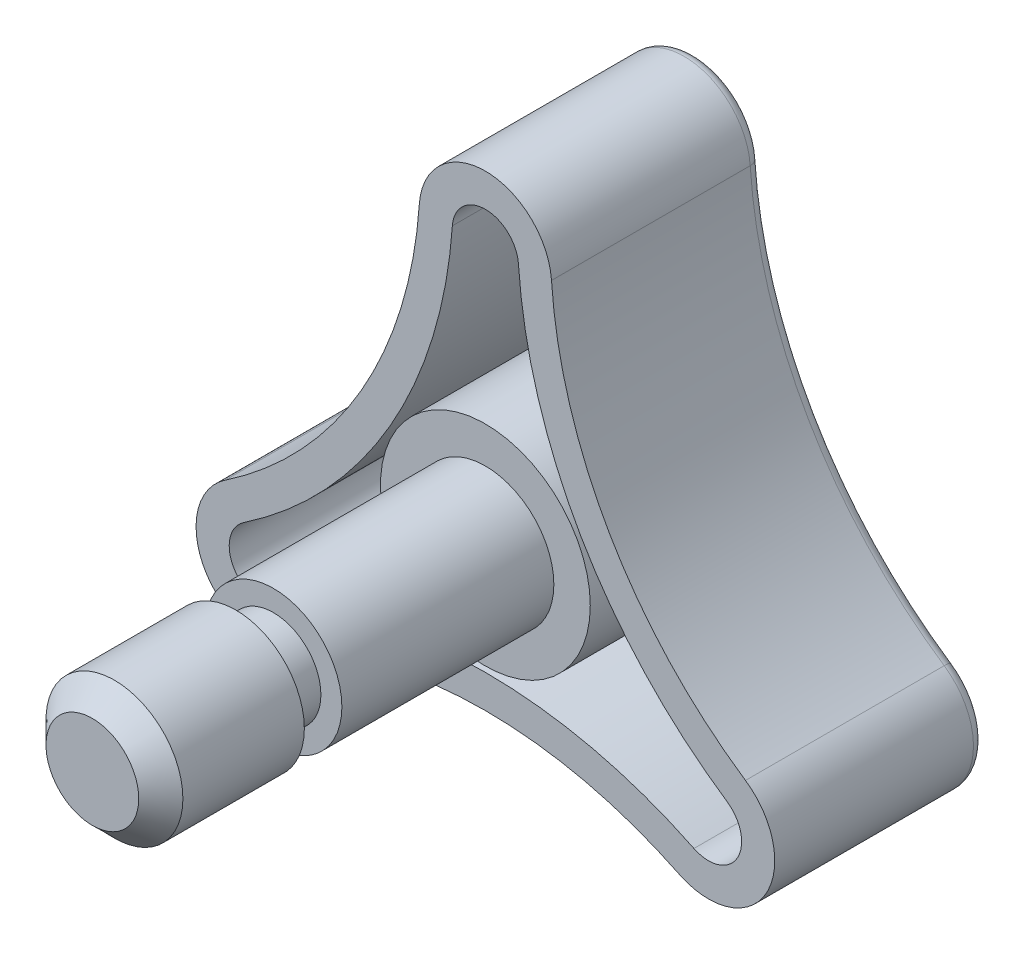
SolidWorks part; units mm, degrees
ref_plane "Front Plane" through (0, 0, 0) normal (0, 0, 1) x (1, 0, 0)
ref_plane "Top Plane" through (0, 0, 0) normal (0, 1, 0) x (1, 0, 0)
ref_plane "Right Plane" through (0, 0, 0) normal (1, 0, 0) x (0, 0, -1)
sketch "Sketch1" plane through (0, 0, 0) normal (0, 0, 1) x (1, 0, 0)
  line L0 (0, 14.6667) -> (0, -7.3333) construction
  line L1 (0, 14.6667) -> (-12.7017, -7.3333) construction
  line L2 (-12.7017, -7.3333) -> (12.7017, -7.3333) construction
  line L3 (12.7017, -7.3333) -> (0, 14.6667) construction
  line L4 (12.7017, -7.3333) -> (-6.3509, 3.6667) construction
  line L5 (-12.7017, -7.3333) -> (6.3509, 3.6667) construction
  line L6 (6.3509, 3.6667) -> (22.9456, 13.2476) construction
  line L7 (-6.3509, 3.6667) -> (-22.9456, 13.2476) construction
  arc A0 (2.9929, 11.8729) -> (-2.9929, 11.8729) centre (0, 11.6667) ccw
  arc A1 (8.7858, -8.5284) -> (11.7787, -3.3445) centre (10.1036, -5.8333) ccw
  arc A2 (-11.7787, -3.3445) -> (-8.7858, -8.5284) centre (-10.1036, -5.8333) ccw
  arc A3 (8.7858, -8.5284) -> (-8.7858, -8.5284) centre (0, -26.4953) ccw
  arc A4 (2.9929, 11.8729) -> (11.7787, -3.3445) centre (22.9456, 13.2476) ccw
  arc A5 (-11.7787, -3.3445) -> (-2.9929, 11.8729) centre (-22.9456, 13.2476) ccw
  point P3 (0, 0)
  point P17 (0, -6.4953)
  dimension "D2" = 6
  dimension "D3" = 20
  dimension "D1" = 22
extrude "Boss-Extrude1" add sketch "Sketch1" along normal blind 9.5
shell "Shell1" thickness 1.5
fillet "Fillet2" radius 0.5 6 edges at (0, 14.6667, 0) (5.6251, 3.2476, 0) (12.7017, -7.3333, 0) (0, -6.4953, 0) (-12.7017, -7.3333, 0) (-5.6251, 3.2476, 0)
sketch "Sketch2" plane through (0, 0, 1.5) normal (0, 0, 1) x (1, 0, 0)
  circle A0 centre (0, 0) radius 4.75
  dimension "D1" = 9.5
extrude "Boss-Extrude2" add sketch "Sketch2" along normal blind 8
sketch "Sketch4" plane through (0, 0, 9.5) normal (0, 0, 1) x (1, 0, 0)
  circle A0 centre (0, 0) radius 3.1
  dimension "D1" = 6.2
extrude "Boss-Extrude3" add sketch "Sketch4" along normal blind 17.8
ref_plane "Plane1" through (0, 0, 20.8) normal (0, 0, 1) x (1, 0, 0)
sketch "Sketch5" plane through (0, 0, 20.8) normal (0, 0, 1) x (1, 0, 0)
  circle A0 centre (0, 0) radius 2.15
  circle A1 centre (0, 0) radius 5
  dimension "D1" = 4.3
  dimension "D2" = 10
extrude "Cut-Extrude1" cut sketch "Sketch5" against normal blind 1.7
chamfer "Chamfer1" distance 1 angle 45 1 edges at (3.1, 0, 27.3)
